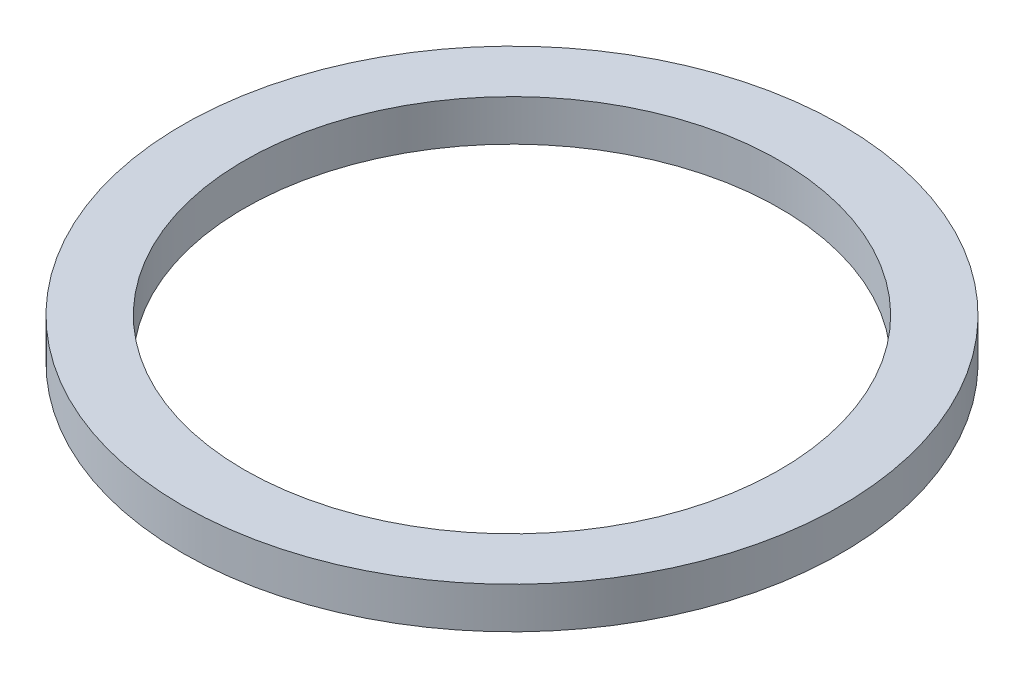
SolidWorks part; units mm, degrees
material "HYPALON"
ref_plane "Front Plane" through (0, 0, 0) normal (0, 0, 1) x (1, 0, 0)
ref_plane "Top Plane" through (0, 0, 0) normal (0, 1, 0) x (1, 0, 0)
ref_plane "Right Plane" through (0, 0, 0) normal (1, 0, 0) x (0, 0, -1)
sketch "Sketch1" plane through (0, 0, 0) normal (0, 1, 0) x (1, 0, 0)
  circle A0 centre (0, 0) radius 4
  circle A1 centre (0, 0) radius 3.25
  dimension "D1" = 8
  dimension "D2" = 6.5
extrude "Boss-Extrude1" add sketch "Sketch1" along normal blind 0.5
